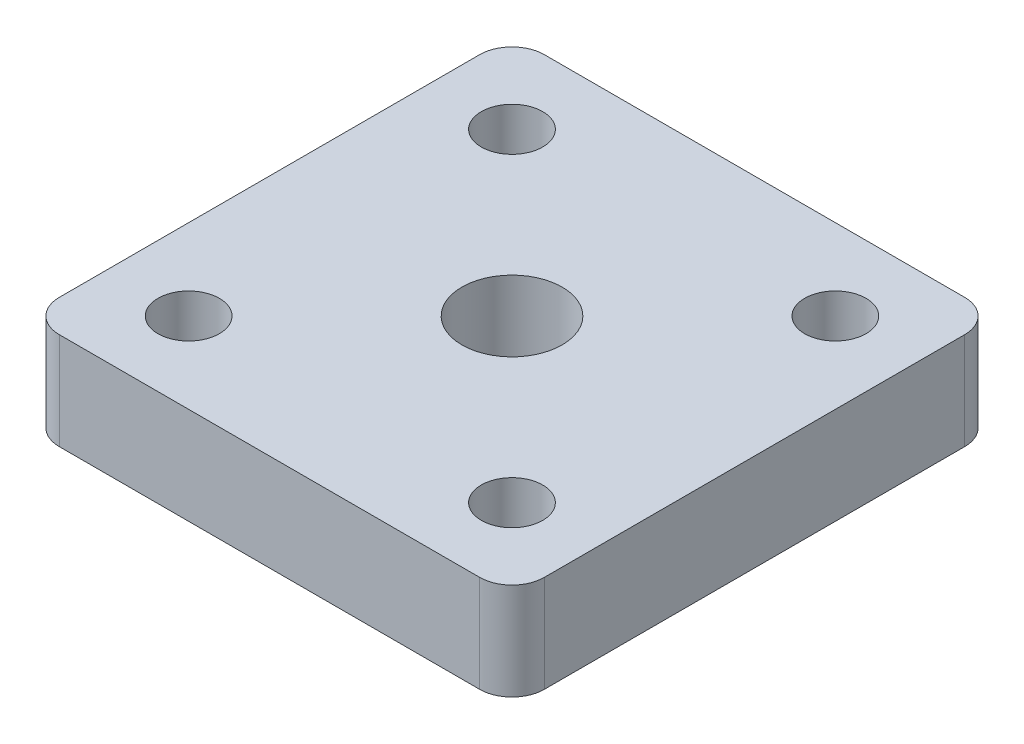
SolidWorks part; units mm, degrees
ref_plane "Front Plane" through (0, 0, 0) normal (0, 0, 1) x (1, 0, 0)
ref_plane "Top Plane" through (0, 0, 0) normal (0, 1, 0) x (1, 0, 0)
ref_plane "Right Plane" through (0, 0, 0) normal (1, 0, 0) x (0, 0, -1)
sketch "Sketch1" plane through (0, 0, 0) normal (0, 1, 0) x (1, 0, 0)
  line L1 (-13, 15) -> (13, 15)
  line L2 (-15, 13) -> (-15, -13)
  line L3 (-13, -15) -> (13, -15)
  line L4 (15, 13) -> (15, -13)
  line L5 (-15, 15) -> (15, -15) construction
  line L6 (-15, -15) -> (15, 15) construction
  arc A0 (13, 15) -> (15, 13) centre (13, 13) cw
  arc A1 (13, -15) -> (15, -13) centre (13, -13) ccw
  arc A2 (-15, -13) -> (-13, -15) centre (-13, -13) ccw
  arc A3 (-13, 15) -> (-15, 13) centre (-13, 13) ccw
  circle A4 centre (0, 0) radius 3.1
  point P0 (0, 0)
  dimension "D3" = 2
  dimension "D4" = 6.2
  dimension "D1" = 30
  dimension "D2" = 30
extrude "Boss-Extrude1" add sketch "Sketch1" along normal blind 6
hole_wizard "#6 Clearance Hole1" positions "Sketch2" profile "Sketch3" hole size "#6" standard "ANSI Inch" end condition through all
sketch "Sketch2" plane through (0, 6, 0) normal (0, 1, 0) x (1, 0, 0)
  point P0 (-10, 10)
  point P2 (10, 10)
  point P4 (-10, -10)
  point P6 (10, -10)
  point P9 (0, 0)
  point P10 (0, 0)
  point P11 (0, 0)
  point P12 (0, 0)
  dimension "D1" = 20
  dimension "D2" = 20
  dimension "D3" = 10
  dimension "D4" = 10
sketch "Sketch3" plane through (-10, 6, -10) normal (1, 0, 0) x (0, 0, 1)
  line L0 (0, 0) -> (0, 6)
  line L1 (0, 6) -> (1.8986, 6)
  line L2 (1.8986, 6) -> (1.8986, 0)
  line L5 (1.8986, 0) -> (0, 0)
  line L11 (0, -6.35) -> (0, 107.95) construction
  dimension "Thru Hole Dia." = 3.7973
  dimension "Thru Hole Depth" = 6
equation "\"D3@Sketch2\"=\"D1@Sketch2\"/2"
equation "\"D4@Sketch2\"=\"D2@Sketch2\"/2"
